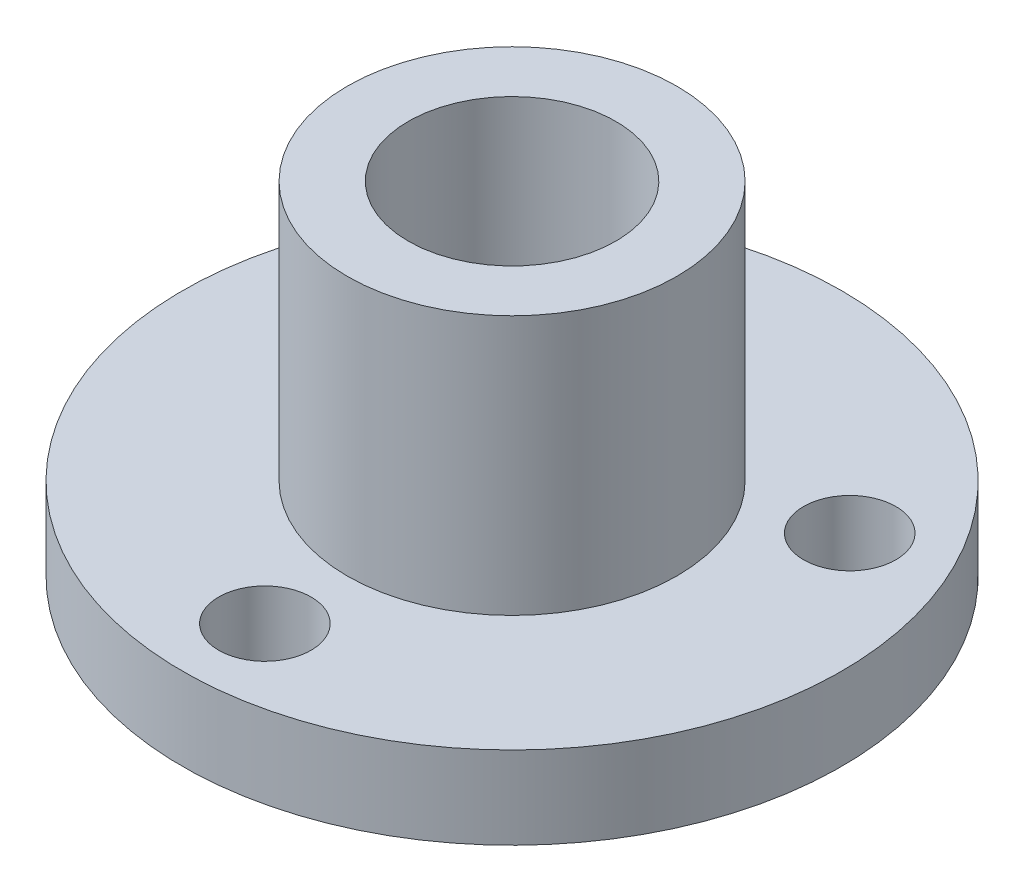
SolidWorks part; units mm, degrees
ref_plane "Front Plane" through (0, 0, 0) normal (0, 0, 1) x (1, 0, 0)
ref_plane "Top Plane" through (0, 0, 0) normal (0, 1, 0) x (1, 0, 0)
ref_plane "Right Plane" through (0, 0, 0) normal (1, 0, 0) x (0, 0, -1)
sketch "Sketch1" plane through (0, 0, 0) normal (0, 1, 0) x (1, 0, 0)
  circle A0 centre (0, 0) radius 12.7
  dimension "D1" = 25.4
extrude "Boss-Extrude1" add sketch "Sketch1" along normal blind 3.18
sketch "Sketch2" plane through (0, 3.18, 0) normal (0, 1, 0) x (1, 0, 0)
  circle A0 centre (0, 0) radius 6.35
  dimension "D1" = 12.7
extrude "Boss-Extrude2" add sketch "Sketch2" along normal blind 10
sketch "Sketch3" plane through (0, 13.18, 0) normal (0, 1, 0) x (1, 0, 0)
  circle A0 centre (0, 0) radius 4
  dimension "D1" = 8
extrude "Cut-Extrude1" cut sketch "Sketch3" against normal through all
sketch "Sketch4" plane through (0, 3.18, 0) normal (0, 1, 0) x (1, 0, 0)
  circle A0 centre (0, 0) radius 9.525 construction
  circle A1 centre (0, -9.525) radius 1.78
  circle A2 centre (-8.2489, 4.7625) radius 1.78
  circle A3 centre (8.2489, 4.7625) radius 1.78
  point P12 (0, 0)
  dimension "D1" = 19.05
  dimension "D2" = 3.56
  dimension "D3" = 3
extrude "Cut-Extrude2" cut sketch "Sketch4" against normal through all
